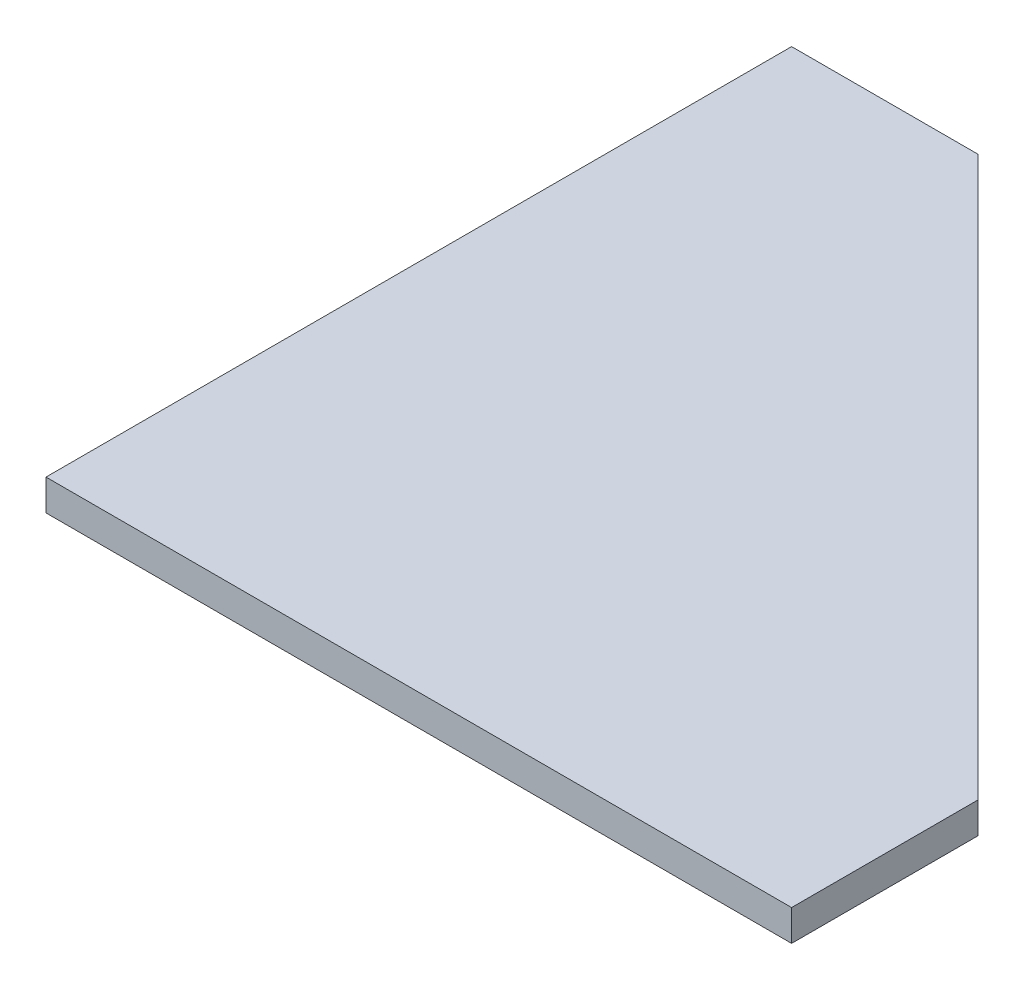
SolidWorks part; units mm, degrees
ref_plane "Front Plane" through (0, 0, 0) normal (0, 0, 1) x (1, 0, 0)
ref_plane "Top Plane" through (0, 0, 0) normal (0, 1, 0) x (1, 0, 0)
ref_plane "Right Plane" through (0, 0, 0) normal (1, 0, 0) x (0, 0, -1)
sketch "Sketch1" plane through (0, 0, 0) normal (0, 1, 0) x (1, 0, 0)
  line L0 (0, 0) -> (0, 152.4)
  line L1 (0, 152.4) -> (38.1, 152.4)
  line L2 (38.1, 152.4) -> (152.4, 38.1)
  line L3 (152.4, 38.1) -> (152.4, 0)
  line L4 (152.4, 0) -> (0, 0)
  line L5 (19.05, 152.4) -> (19.05, 0) construction
  line L6 (152.4, 19.05) -> (0, 19.05) construction
  point P10 (19.05, 133.35)
  point P11 (19.05, 95.25)
  point P12 (19.05, 57.15)
  point P13 (19.05, 19.05)
  point P14 (57.15, 19.05)
  point P15 (95.25, 19.05)
  point P16 (133.35, 19.05)
  dimension "D1" = 152.4
  dimension "D2" = 152.4
  dimension "D3" = 38.1
  dimension "D4" = 38.1
  dimension "D5" = 38.1
  dimension "D6" = 38.1
  dimension "D7" = 38.1
  dimension "D8" = 38.1
  dimension "D9" = 38.1
  dimension "D10" = 38.1
extrude "Extrude1" add sketch "Sketch1" along normal blind 6.35
